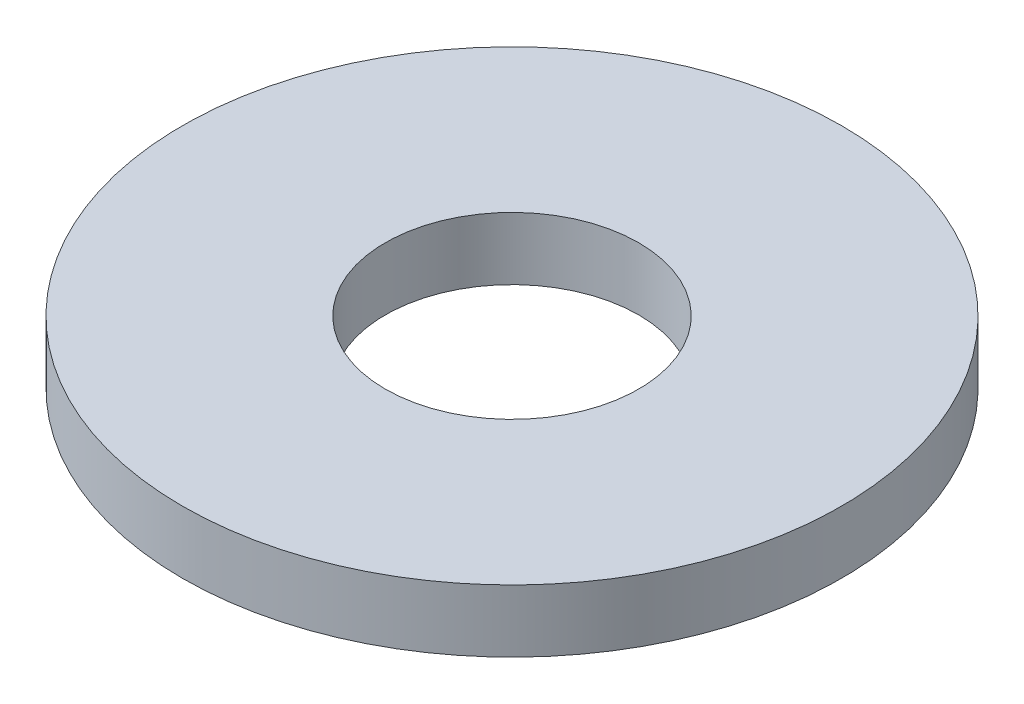
SolidWorks part; units mm, degrees
material "Acier allié"
ref_plane "Plan de face" through (0, 0, 0) normal (0, 0, 1) x (1, 0, 0)
ref_plane "Plan de dessus" through (0, 0, 0) normal (0, 1, 0) x (1, 0, 0)
ref_plane "Plan de droite" through (0, 0, 0) normal (1, 0, 0) x (0, 0, -1)
sketch "Esquisse1" plane through (0, 0, 0) normal (0, 1, 0) x (1, 0, 0)
  circle A0 centre (0, 0) radius 3.9
  circle A1 centre (0, 0) radius 1.5
  dimension "D1" = 7.8
  dimension "D2" = 3
extrude "Boss.-Extru.1" add sketch "Esquisse1" along normal blind 0.74
